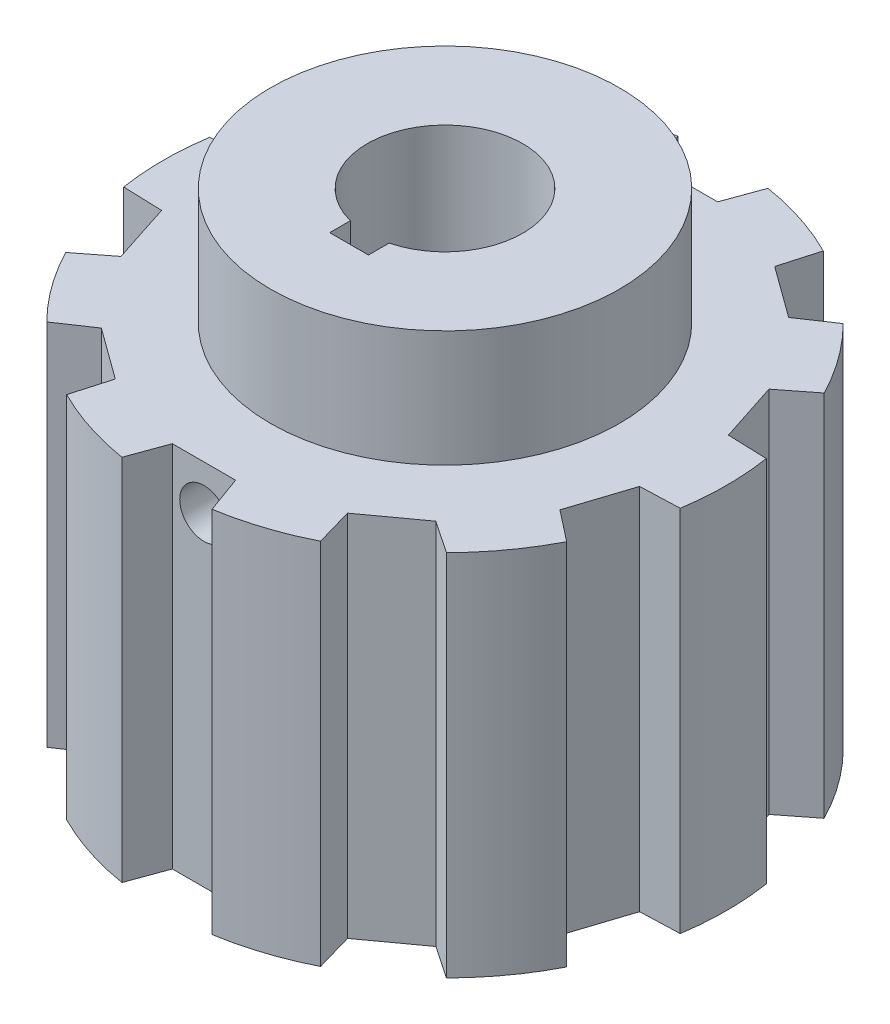
SolidWorks part; units mm, degrees
ref_plane "Front Plane" through (0, 0, 0) normal (0, 0, 1) x (1, 0, 0)
ref_plane "Top Plane" through (0, 0, 0) normal (0, 1, 0) x (1, 0, 0)
ref_plane "Right Plane" through (0, 0, 0) normal (1, 0, 0) x (0, 0, -1)
sketch "Sketch2" plane through (0, 0, 0) normal (0, 1, 0) x (1, 0, 0)
  line L0 (7.3355, -10.3439) -> (9.9741, -8.4269)
  line L1 (9.9741, -8.4269) -> (11.6548, -9.5605)
  line L2 (14.2651, -5.9678) -> (12.6676, -4.7197)
  line L3 (12.6676, -4.7197) -> (13.6754, -1.6178)
  line L4 (13.6754, -1.6178) -> (15.7014, -1.5471)
  line L5 (15.7014, 2.8938) -> (13.6754, 2.9645)
  line L6 (13.6754, 2.9645) -> (12.6676, 6.0664)
  line L7 (12.6676, 6.0664) -> (14.2651, 7.3145)
  line L8 (11.6548, 10.9072) -> (9.9741, 9.7736)
  line L9 (9.9741, 9.7736) -> (7.3355, 11.6906)
  line L10 (7.3355, 11.6906) -> (7.8943, 13.6394)
  line L11 (3.6708, 15.0117) -> (2.9775, 13.1067)
  line L12 (2.9775, 13.1067) -> (-0.284, 13.1067)
  line L13 (-0.284, 13.1067) -> (-0.9774, 15.0117)
  line L14 (-5.2009, 13.6394) -> (-4.6421, 11.6906)
  line L15 (-4.6421, 11.6906) -> (-7.2807, 9.7736)
  line L16 (-7.2807, 9.7736) -> (-8.9614, 10.9072)
  line L17 (-11.5716, 7.3145) -> (-9.9741, 6.0664)
  line L18 (-9.9741, 6.0664) -> (-10.982, 2.9645)
  line L19 (-10.982, 2.9645) -> (-13.008, 2.8938)
  line L20 (-13.008, -1.5471) -> (-10.982, -1.6178)
  line L21 (-10.982, -1.6178) -> (-9.9741, -4.7197)
  line L22 (-9.9741, -4.7197) -> (-11.5716, -5.9678)
  line L23 (-8.9614, -9.5605) -> (-7.2807, -8.4269)
  line L24 (-7.2807, -8.4269) -> (-4.6421, -10.3439)
  line L25 (-4.6421, -10.3439) -> (-5.2009, -12.2926)
  line L26 (-0.9774, -13.6649) -> (-0.284, -11.7599)
  line L27 (-0.284, -11.7599) -> (2.9775, -11.7599)
  line L28 (2.9775, -11.7599) -> (3.6708, -13.6649)
  line L29 (7.8943, -12.2926) -> (7.3355, -10.3439)
  arc A0 (11.6548, -9.5605) -> (14.2651, -5.9678) centre (1.3467, 0.6734) ccw
  arc A1 (15.7014, -1.5471) -> (15.7014, 2.8938) centre (1.3467, 0.6734) ccw
  arc A2 (14.2651, 7.3145) -> (11.6548, 10.9072) centre (1.3467, 0.6734) ccw
  arc A3 (7.8943, 13.6394) -> (3.6708, 15.0117) centre (1.3467, 0.6734) ccw
  arc A4 (-0.9774, 15.0117) -> (-5.2009, 13.6394) centre (1.3467, 0.6734) ccw
  arc A5 (-8.9614, 10.9072) -> (-11.5716, 7.3145) centre (1.3467, 0.6734) ccw
  arc A6 (-13.008, 2.8938) -> (-13.008, -1.5471) centre (1.3467, 0.6734) ccw
  arc A7 (-11.5716, -5.9678) -> (-8.9614, -9.5605) centre (1.3467, 0.6734) ccw
  arc A8 (-5.2009, -12.2926) -> (-0.9774, -13.6649) centre (1.3467, 0.6734) ccw
  arc A9 (3.6708, -13.6649) -> (7.8943, -12.2926) centre (1.3467, 0.6734) ccw
extrude "Boss-Extrude1" add sketch "Sketch2" along normal blind 19
sketch "Sketch3" plane through (0, 19, 0) normal (0, 1, 0) x (1, 0, 0)
  line L0 (1.3467, 13.1067) -> (1.3467, -11.7599) construction
  line L1 (2.9775, 13.1067) -> (-0.284, 13.1067) construction
  line L2 (-0.284, -11.7599) -> (2.9775, -11.7599) construction
  line L3 (13.1715, 4.5155) -> (-10.4781, -3.1687) construction
  line L4 (13.6754, 2.9645) -> (12.6676, 6.0664) construction
  line L5 (-10.982, -1.6178) -> (-9.9741, -4.7197) construction
  line L6 (8.6548, -9.3854) -> (-5.9614, 10.7321) construction
  line L7 (7.3355, -10.3439) -> (9.9741, -8.4269) construction
  line L8 (-4.6421, 11.6906) -> (-7.2807, 9.7736) construction
  circle A0 centre (1.3467, 0.6734) radius 4.01
  point P18 (1.3467, 0.6734)
  dimension "D1" = 8.02
extrude "Cut-Extrude1" cut sketch "Sketch3" against normal through all
sketch "Sketch5" plane through (0, 19, 0) normal (0, 1, 0) x (1, 0, 0)
  circle A0 centre (1.3467, 0.6734) radius 4.01 construction
  circle A1 centre (1.3467, 0.6734) radius 4.01
  circle A2 centre (1.3467, 0.6734) radius 9
  dimension "D1" = 18
extrude "Boss-Extrude2" add sketch "Sketch5" along normal blind 6
sketch "Sketch6" plane through (0, 25, 0) normal (0, 1, 0) x (1, 0, 0)
  line L0 (1.3467, 9.6734) -> (1.3467, -8.3266) construction
  line L2 (0.3467, -0.4595) -> (2.3467, -0.4595)
  line L3 (0.3467, -0.4595) -> (0.3467, -4.2755)
  line L4 (0.3467, -4.2755) -> (2.3467, -4.2755)
  line L5 (2.3467, -0.4595) -> (2.3467, -4.2755)
  line L6 (0.3467, -0.4595) -> (2.3467, -4.2755) construction
  line L7 (0.3467, -4.2755) -> (2.3467, -0.4595) construction
  circle A0 centre (1.3467, 0.6734) radius 9 construction
  circle A1 centre (1.3467, 0.6734) radius 3.4511 construction
  point P7 (1.3467, 4.1245)
  point P8 (1.3467, -2.3675)
  dimension "D1" = 2
  dimension "D2" = 8.4
extrude "Cut-Extrude3" cut sketch "Sketch6" against normal through all
ref_plane "Plane1" through (0, 0, 1.2755) normal (0, 0, -1) x (-1, 0, 0)
sketch "Sketch9" plane through (0, 0, 1.2755) normal (0, 0, -1) x (-1, 0, 0)
  line L0 (-1.3467, 25) -> (-1.3467, 0) construction
  line L1 (7.6533, 25) -> (-10.3467, 25) construction
  line L2 (-2.9775, 0) -> (0.284, 0) construction
  line L3 (-2.9775, 19) -> (0.284, 19) construction
  point P6 (-1.3467, 16.7)
  dimension "D1" = 2.3
hole_wizard "M3x0.5 Tapped Hole2" positions "3DSketch2" profile "Sketch10" tap size "M3x0.5" standard "ANSI Metric"
sketch3d "3DSketch2"
  point P0 (1.3467, 16.7, 1.2755)
sketch "Sketch10" plane through (1.3467, 16.7, 1.2755) normal (1, 0, 0) x (0, 1, 0)
  line L0 (0, 0) -> (0, 12.3894)
  line L1 (0, 12.3894) -> (1.25, 12.3894)
  line L2 (1.25, 12.3894) -> (1.25, 0)
  line L5 (1.25, 0) -> (0, 0)
  line L11 (0, -6.35) -> (0, 107.95) construction
  dimension "Thru Tap Drill Dia." = 2.5
  dimension "Thru Tap Drill Depth" = 12.3894
cosmetic thread "Hole Thread2" parameters "D2"=3
